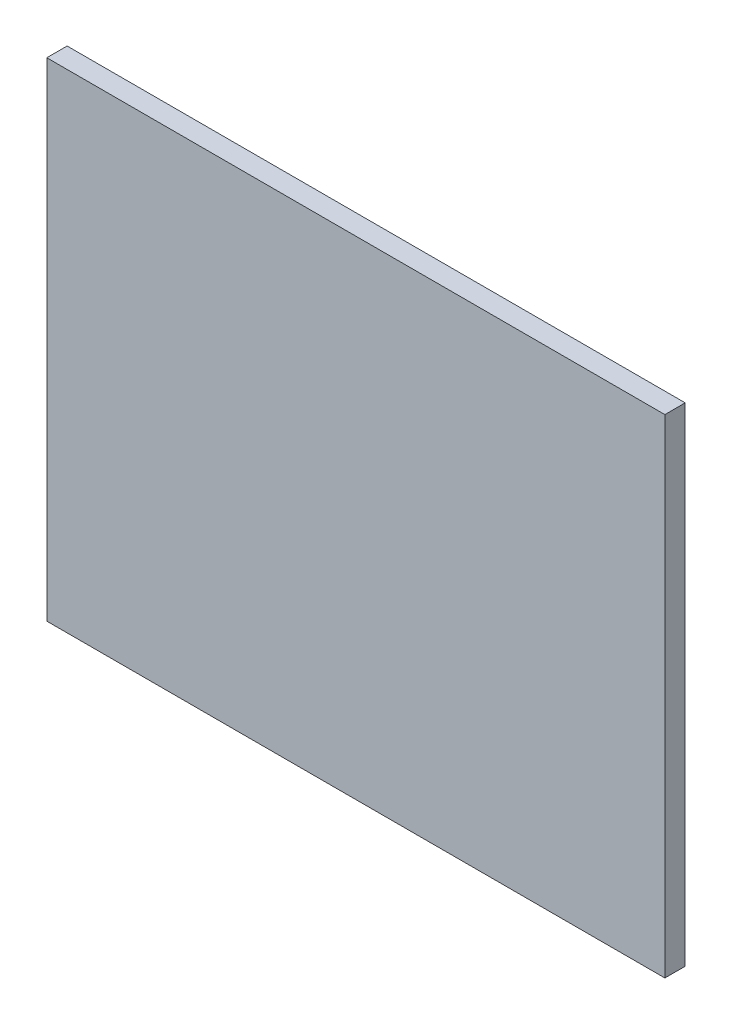
SolidWorks part; units mm, degrees
ref_plane "前视基准面" through (0, 0, 0) normal (0, 0, 1) x (1, 0, 0)
ref_plane "上视基准面" through (0, 0, 0) normal (0, 1, 0) x (1, 0, 0)
ref_plane "右视基准面" through (0, 0, 0) normal (1, 0, 0) x (0, 0, -1)
other "Configuration Table"
sketch "草图1" plane through (0, 0, 0) normal (0, 0, 1) x (1, 0, 0)
  line L1 (0, 0) -> (76, 0)
  line L2 (0, 0) -> (0, -60)
  line L3 (0, -60) -> (76, -60)
  line L4 (76, 0) -> (76, -60)
extrude "凸台-拉伸1" add sketch "草图1" along normal blind 2.5
